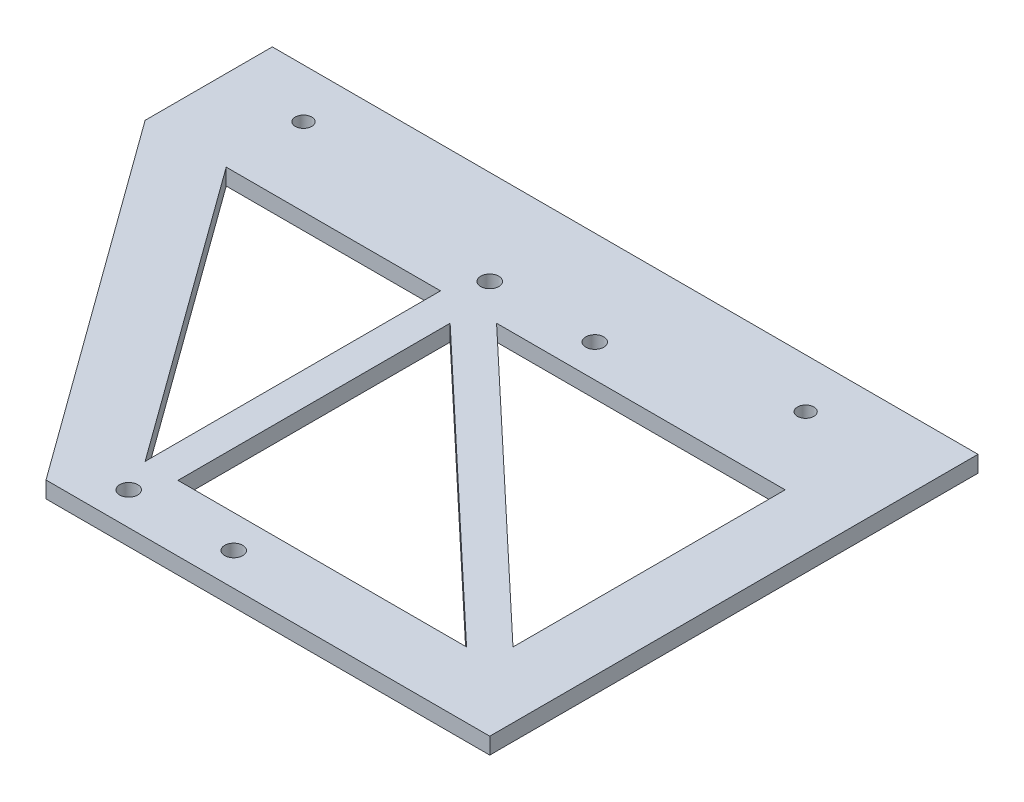
SolidWorks part; units mm, degrees
ref_plane "Front Plane" through (0, 0, 0) normal (0, 0, 1) x (1, 0, 0)
ref_plane "Top Plane" through (0, 0, 0) normal (0, 1, 0) x (1, 0, 0)
ref_plane "Right Plane" through (0, 0, 0) normal (1, 0, 0) x (0, 0, -1)
sketch "Sketch1" plane through (0, 0, 0) normal (0, 1, 0) x (1, 0, 0)
  line L3 (135.1994, 0) -> (0, 0)
  line L4 (10.1994, 65) -> (135.1994, 65) construction
  line L5 (20.1994, 102.9259) -> (108.1253, 20)
  line L10 (27.2735, 110) -> (20.1994, 110) construction
  line L11 (27.2735, 110) -> (115.1994, 27.0741)
  line L12 (27.2735, 110) -> (115.1994, 110)
  line L13 (115.1994, 110) -> (115.1994, 27.0741)
  line L14 (108.1253, 20) -> (20.1994, 20)
  line L15 (20.1994, 20) -> (20.1994, 102.9259)
  line L16 (20.1994, 110) -> (20.1994, 102.9259) construction
  line L17 (115.1994, 27.0741) -> (115.1994, 20) construction
  line L18 (115.1994, 20) -> (108.1253, 20) construction
  line L19 (-79.8006, 148.75) -> (135.1994, 148.75)
  line L20 (135.1994, 0) -> (135.1994, 148.75)
  line L22 (-79.8006, 110) -> (-79.8006, 148.75)
  line L24 (-79.8006, 110) -> (0, 0)
  line L25 (-55.0919, 110) -> (10.1994, 20)
  line L26 (-55.0919, 110) -> (10.1994, 110)
  line L27 (10.1994, 110) -> (10.1994, 20)
  circle A0 centre (15.1994, 10) radius 2.75
  circle A1 centre (47.1994, 10) radius 2.75
  circle A2 centre (15.1994, 120) radius 2.75
  circle A3 centre (47.1994, 120) radius 2.75
  circle A4 centre (-55.3006, 133.75) radius 2.5
  circle A5 centre (97.6994, 133.75) radius 2.5
  point P30 (0, 0)
  point P31 (0, 0)
  point P32 (0, 0)
  point P33 (0, 0)
  point P35 (0, 0)
  dimension "D2" = 5.5
  dimension "D3" = 110
  dimension "D4" = 32
  dimension "D5" = 55
  dimension "D6" = 38.75
  dimension "D14" = 24.5
  dimension "D15" = 15
  dimension "D16" = 5
  dimension "D17" = 5
  dimension "D18" = 37.5
  dimension "D19" = 10
  dimension "D20" = 45
  dimension "D7" = 215
  dimension "D8" = 10
  dimension "D9" = 20
  dimension "D10" = 15.1994
  dimension "D11" = 20
  dimension "D12" = 20
  dimension "D13" = 10
extrude "Boss-Extrude2" add sketch "Sketch1" along normal blind 5
